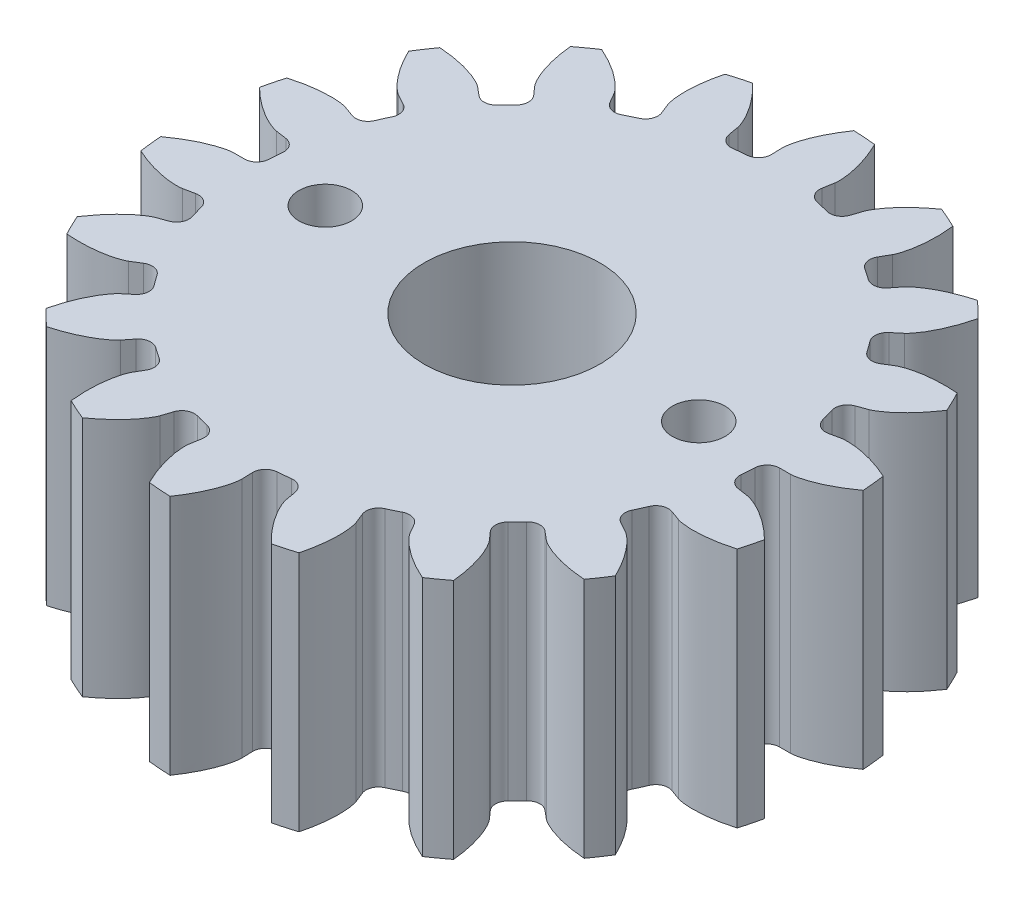
SolidWorks part; units mm, degrees
material "ABS"
ref_plane "Plan de face" through (0, 0, 0) normal (0, 0, 1) x (1, 0, 0)
ref_plane "Plan de dessus" through (0, 0, 0) normal (0, 1, 0) x (1, 0, 0)
ref_plane "Plan de droite" through (0, 0, 0) normal (1, 0, 0) x (0, 0, -1)
sketch "Esquisse1" plane through (0, 0, 0) normal (0, 1, 0) x (1, 0, 0)
  circle A0 centre (0, 0) radius 15
  circle A1 centre (0, 0) radius 11.625 construction
  circle A2 centre (0, 0) radius 13.5 construction
  circle A6 centre (0, 0) radius 12.6859 construction
  dimension "D1" = 27
  dimension "D5" = 1.5
  dimension "D6" = 1.875
  dimension "D7" = 25.3717
  dimension "D11" = 30
extrude "Boss.-Extru.1" add sketch "Esquisse1" along normal blind 11
sketch "Esquisse3" plane through (0, 0, 0) normal (0, 1, 0) x (1, 0, 0)
  spline S2 degree 4 poles (12.6859, 0) (12.6952, 0.0002) (12.7215, 0.0014) (12.7711, 0.006) (12.8517, 0.017) (12.9537, 0.036) (13.0846, 0.0664) (13.2374, 0.1094) (13.4034, 0.1643) (13.5818, 0.2322) (13.7575, 0.3069) (13.9305, 0.388) (14.1005, 0.4746) (14.3038, 0.5863) (14.5434, 0.7296) (14.8169, 0.9104) (15.1191, 1.1309) (15.4176, 1.3716) (15.7034, 1.6215) (15.9822, 1.8883) (16.2448, 2.1567) (16.5067, 2.4493) (16.7429, 2.7266) (16.9946, 3.0518) (17.1941, 3.3187) (17.4429, 3.6856) (17.5855, 3.9066) (17.7472, 4.1702) (17.8163, 4.2898) (17.859, 4.3634) knots 0 0 0 0 0 0.005377 0.015084 0.028532 0.04661 0.064855 0.092111 0.119476 0.146842 0.174209 0.201575 0.228941 0.256307 0.307035 0.361767 0.4165 0.471232 0.525964 0.580697 0.635429 0.690161 0.744894 0.799626 0.854358 0.909091 0.954545 1 1 1 1 1 construction
  spline S3 degree 4 poles (12.6859, 0) (12.6952, 0.0002) (12.7215, 0.0014) (12.7711, 0.006) (12.8517, 0.017) (12.9537, 0.036) (13.0846, 0.0664) (13.2374, 0.1094) (13.4034, 0.1643) (13.5818, 0.2322) (13.7575, 0.3069) (13.9305, 0.388) (14.1005, 0.4746) (14.3038, 0.5863) (14.5434, 0.7296) (14.8169, 0.9104) (15.1191, 1.1309) (15.4176, 1.3716) (15.7034, 1.6215) (15.9822, 1.8883) (16.2448, 2.1567) (16.5067, 2.4493) (16.7429, 2.7266) (16.9946, 3.0518) (17.1941, 3.3187) (17.3889, 3.606) (17.4821, 3.7475) (17.529, 3.8206) knots 0 0 0 0 0 0.005377 0.015084 0.028532 0.04661 0.064855 0.092111 0.119476 0.146842 0.174209 0.201575 0.228941 0.256307 0.307035 0.361767 0.4165 0.471232 0.525964 0.580697 0.635429 0.690161 0.744894 0.799626 0.854358 0.909091 0.909091 0.909091 0.909091 0.909091
sketch "Esquisse5" plane through (0, 0, 0) normal (0, 1, 0) x (1, 0, 0)
  line L0 (0, 0) -> (13.4647, -0.976) construction
  line L1 (12.6859, 0) -> (11.625, 0)
  line L2 (12.5532, -1.8295) -> (11.5035, -1.6766)
  circle A0 centre (0, 0) radius 11.625 construction
  arc A1 (11.5035, -1.6766) -> (11.625, 0) centre (0, 0) ccw
  circle A2 centre (0, 0) radius 13.5 construction
  spline S1 degree 4 poles (-4.6153, 1999.7043) (9.8867, 29.0764) (10.9116, 0.4774) (11.9105, -0.1115) (12.8517, 0.017) (12.9537, 0.036) (13.0846, 0.0664) (13.2374, 0.1094) (13.4034, 0.1643) (13.5818, 0.2322) (13.7575, 0.3069) (13.9305, 0.388) (14.1005, 0.4746) (14.3038, 0.5863) (14.5434, 0.7296) (14.8169, 0.9104) (15.1191, 1.1309) (15.4176, 1.3716) (15.7034, 1.6215) (15.9822, 1.8883) (16.2448, 2.1567) (16.5067, 2.4493) (16.7429, 2.7266) (16.9946, 3.0518) (17.9626, 4.3469) (20.585, 8.859) (-12.9238, -42.5101) (1097.0378, 1687.289) knots -0.497849 -0.497849 -0.497849 -0.497849 -0.497849 0.005377 0.015084 0.028532 0.04661 0.064855 0.092111 0.119476 0.146842 0.174209 0.201575 0.228941 0.256307 0.307035 0.361767 0.4165 0.471232 0.525964 0.580697 0.635429 0.690161 0.744894 0.799626 0.854358 1.752643 1.752643 1.752643 1.752643 1.752643 only from (12.6859, 0) to (17.529, 3.8206) construction
  spline S2 degree 4 poles (12.6859, 0) (12.6952, 0.0002) (12.7215, 0.0014) (12.7711, 0.006) (12.8517, 0.017) (12.9537, 0.036) (13.0846, 0.0664) (13.2374, 0.1094) (13.4034, 0.1643) (13.5818, 0.2322) (13.7575, 0.3069) (13.9305, 0.388) (14.1005, 0.4746) (14.3038, 0.5863) (14.5434, 0.7296) (14.8169, 0.9104) (15.1191, 1.1309) (15.4176, 1.3716) (15.7034, 1.6215) (15.9822, 1.8883) (16.2448, 2.1567) (16.5067, 2.4493) (16.7429, 2.7266) (16.9946, 3.0518) (17.1941, 3.3187) (17.3889, 3.606) (17.4821, 3.7475) (17.529, 3.8206) knots 0 0 0 0 0 0.005377 0.015084 0.028532 0.04661 0.064855 0.092111 0.119476 0.146842 0.174209 0.201575 0.228941 0.256307 0.307035 0.361767 0.4165 0.471232 0.525964 0.580697 0.635429 0.690161 0.744894 0.799626 0.854358 0.909091 0.909091 0.909091 0.909091 0.909091
  spline S3 degree 4 poles (12.5532, -1.8295) (12.5625, -1.8311) (12.5883, -1.836) (12.6367, -1.8478) (12.7149, -1.8703) (12.8131, -1.9038) (12.9383, -1.9527) (13.0832, -2.0174) (13.2396, -2.0956) (13.4063, -2.1885) (13.5694, -2.2878) (13.7289, -2.393) (13.8847, -2.5033) (14.0697, -2.6431) (14.2861, -2.8194) (14.5307, -3.0378) (14.7979, -3.2995) (15.0586, -3.5808) (15.3053, -3.8693) (15.5428, -4.1735) (15.764, -4.4769) (15.9809, -4.8043) (16.1746, -5.1127) (16.3768, -5.4709) (16.5357, -5.7637) (16.6871, -6.0761) (16.7588, -6.2296) (16.7947, -6.3087) knots 0 0 0 0 0 0.005377 0.015084 0.028532 0.04661 0.064855 0.092111 0.119476 0.146842 0.174209 0.201575 0.228941 0.256307 0.307035 0.361767 0.4165 0.471232 0.525964 0.580697 0.635429 0.690161 0.744894 0.799626 0.854358 0.909091 0.909091 0.909091 0.909091 0.909091
  point P6 (13.4985, 0.2012)
  dimension "D1" = 5
extrude "Enlèv. mat.-Extru.1" cut sketch "Esquisse5" against normal through all and the other way through all
fillet "Congé1" radius 0.57 2 edges at (11.5035, 5.5, 1.6766) (11.625, 5.5, 0)
pattern_circular "Répétition circulaire1" count 18 over 360 about axis through (0, 11, 0) along (0, 1, 0) of "Enlèv. mat.-Extru.1", "Congé1"
sketch "Esquisse6" plane through (0, 11, 0) normal (0, 1, 0) x (1, 0, 0)
  line L0 (-8.5, 0) -> (8.5, 0) construction
  circle A0 centre (0, 0) radius 4
  circle A1 centre (-8.5, 0) radius 1.2
  circle A2 centre (8.5, 0) radius 1.2
  dimension "D1" = 8
  dimension "D2" = 17
  dimension "D3" = 2.4
extrude "Enlèv. mat.-Extru.2" cut sketch "Esquisse6" against normal through all
equation "\"D1@Esquisse1\"= \"Module\" * \"Z1\""
equation "\"Module\"= 1.5'module"
equation "\"Z1\"= 18'nb de dents"
equation "\"D5@Esquisse1\"=\"Module\""
equation "\"D6@Esquisse1\"=\"Module\"*1.25"
equation "\"a\"= 20'angle pression"
equation "\"D7@Esquisse1\"=\"D1@Esquisse1\"*cos( \"a\")"
equation "\"rayon\"= \"Module\" * 0.38'R fond de dent"
equation "\"D1@Esquisse5\"=360/\"Z1\"/4"
equation "\"D1@Répétition circulaire1\"=\"Z1\""
equation "\"D1@Congé1\"=\"rayon\""
